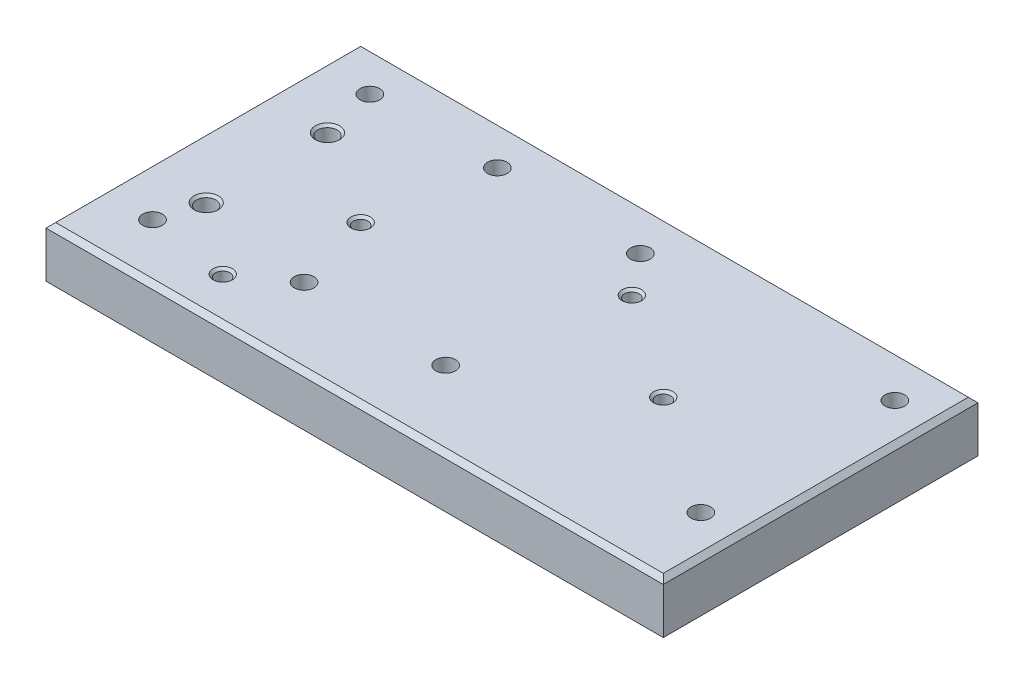
SolidWorks part; units mm, degrees
material "201.0-T6 Insulated Mold Casting (SS)"
ref_plane "Front Plane" through (0, 0, 0) normal (0, 0, 1) x (1, 0, 0)
ref_plane "Top Plane" through (0, 0, 0) normal (0, 1, 0) x (1, 0, 0)
ref_plane "Right Plane" through (0, 0, 0) normal (1, 0, 0) x (0, 0, -1)
sketch "Sketch1" plane through (0, 0, 0) normal (0, 1, 0) x (1, 0, 0)
  line L0 (5, 5) -> (5, 125) construction
  line L1 (0, 0) -> (255, 0)
  line L2 (0, 0) -> (0, 130)
  line L3 (0, 130) -> (255, 130)
  line L4 (255, 0) -> (255, 130)
  line L5 (5, 125) -> (250, 125) construction
  line L6 (250, 5) -> (250, 125) construction
  line L7 (5, 5) -> (250, 5) construction
  line L8 (100, 139.2727) -> (100, -52.6625) construction
  line L9 (26.03, 136.0866) -> (26.03, 17.2333) construction
  line L10 (239, 136.0866) -> (239, -5.597) construction
  line L11 (21, 139.2727) -> (21, -5.597) construction
  line L12 (250, 65) -> (5, 65) construction
  line L13 (7, 136.0866) -> (7, -35.5718) construction
  line L21 (33, 136.8797) -> (33, -52.6625) construction
  line L22 (33, -52.6625) -> (167, -52.6625) construction
  line L23 (167, 136.8797) -> (167, -52.6625) construction
  circle A0 centre (73.68, 112.78) radius 4.05
  circle A1 centre (133.87, 111.67) radius 4.05
  circle A2 centre (133.61, 31.48) radius 4.05
  circle A3 centre (74.69, 31.92) radius 4.05
  circle A4 centre (26.03, 90.25) radius 4
  circle A5 centre (26.03, 40.14) radius 4
  circle A6 centre (21, 112.78) radius 4.05
  circle A7 centre (239, 111.67) radius 4.05
  circle A8 centre (239, 31.48) radius 4.05
  circle A9 centre (21, 23) radius 4.05
  circle A10 centre (65, 65) radius 3
  circle A11 centre (190, 65) radius 3
  circle A12 centre (147, 95) radius 3
  circle A13 centre (55, 18) radius 3
  point P43 (25, 136.0866)
  point P44 (25, -5.597)
  dimension "D5" = 8.1
  dimension "D6" = 8.1
  dimension "D7" = 8.1
  dimension "D8" = 8.1
  dimension "D16" = 8
  dimension "D17" = 8
  dimension "D23" = 8.1
  dimension "D24" = 8.1
  dimension "D25" = 8.1
  dimension "D26" = 8.1
  dimension "D28" = 60
  dimension "D32" = 6
  dimension "D33" = 6
  dimension "D31" = 6
  dimension "D37" = 30
  dimension "D39" = 6
  dimension "D1" = 255
  dimension "D2" = 130
  dimension "D4" = 95
  dimension "D9" = 12.22
  dimension "D10" = 68.68
  dimension "D11" = 69.69
  dimension "D12" = 128.87
  dimension "D13" = 13.33
  dimension "D14" = 128.61
  dimension "93.08" = 93.08
  dimension "D15" = 93.52
  dimension "D18" = 34.75
  dimension "D19" = 84.86
  dimension "D20" = 21.03
  dimension "D21" = 234
  dimension "D22" = 16
  dimension "D27" = 102
  dimension "D29" = 125
  dimension "D34" = 107
  dimension "D35" = 50
  dimension "D30" = 67
  dimension "D36" = 134
  dimension "D38" = 142
  dimension "D40" = 160
  dimension "D3" = 5
extrude "Boss-Extrude1" add sketch "Sketch1" against normal blind 21
chamfer "Chamfer1" distance 2 angle 45 4 edges at (127.5, 0, 0) (255, 0, -65) (127.5, 0, -130) (0, 0, -65)
chamfer "Chamfer5" distance 1 angle 45 4 edges at (190, 0, -62) (65, 0, -62) (147, 0, -92) (55, 0, -15)
chamfer "Chamfer6" distance 1 angle 45 2 edges at (26.03, 0, -36.14) (26.03, 0, -86.25)
